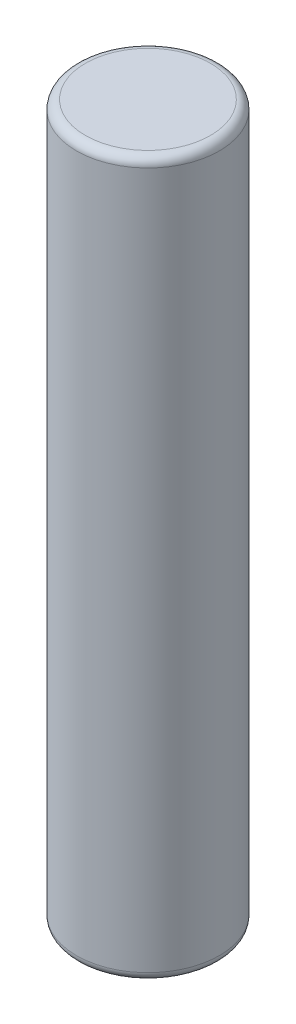
SolidWorks part; units mm, degrees
ref_plane "Front Plane" through (0, 0, 0) normal (0, 0, 1) x (1, 0, 0)
ref_plane "Top Plane" through (0, 0, 0) normal (0, 1, 0) x (1, 0, 0)
ref_plane "Right Plane" through (0, 0, 0) normal (1, 0, 0) x (0, 0, -1)
sketch "Sketch1" plane through (0, 0, 0) normal (0, 1, 0) x (1, 0, 0)
  circle A0 centre (0, 0) radius 4
  dimension "D1" = 8
extrude "Boss-Extrude1" add sketch "Sketch1" along normal blind 40
fillet "Fillet1" radius 0.5 2 edges at (0, 0, 4) (0, 40, 4)
